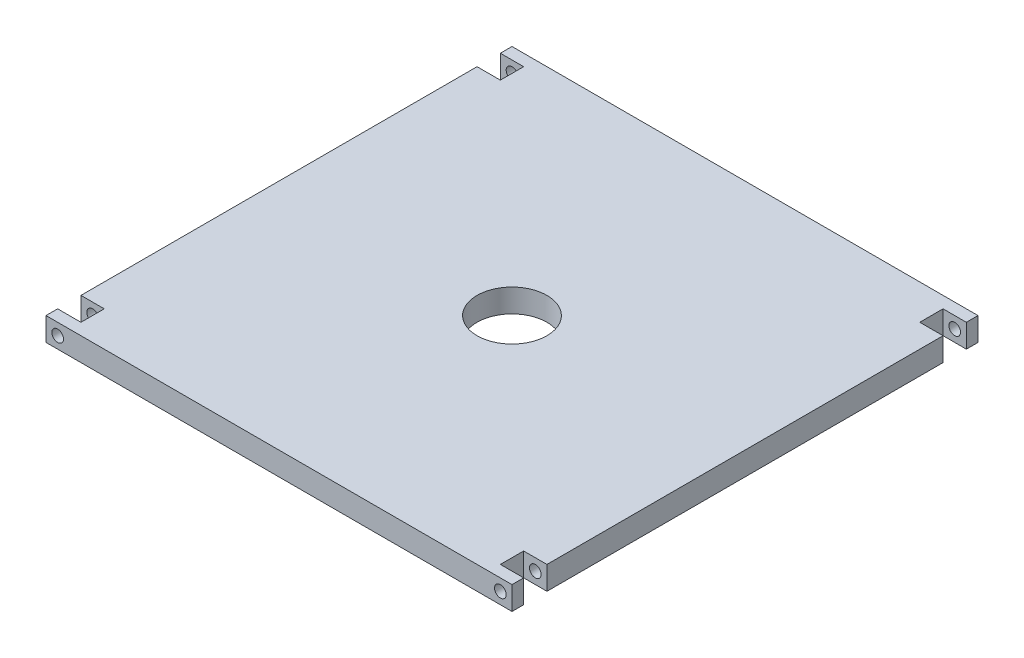
SolidWorks part; units mm, degrees
ref_plane "Plan de face" through (0, 0, 0) normal (0, 0, 1) x (1, 0, 0)
ref_plane "Plan de dessus" through (0, 0, 0) normal (0, 1, 0) x (1, 0, 0)
ref_plane "Plan de droite" through (0, 0, 0) normal (1, 0, 0) x (0, 0, -1)
sketch "Esquisse1" plane through (0, 0, 0) normal (0, 1, 0) x (1, 0, 0)
  line L0 (-100, 95) -> (-90, 95)
  line L1 (100, 100) -> (-100, 100)
  line L2 (100, 100) -> (100, 95)
  line L3 (100, -100) -> (15, -100)
  line L4 (-100, 100) -> (-100, 95)
  line L5 (100, 100) -> (-100, -100) construction
  line L6 (100, -100) -> (-100, 100) construction
  line L7 (-90, 95) -> (-90, 85)
  line L8 (-90, 85) -> (-100, 85)
  line L9 (-100, 85) -> (-100, -85)
  line L10 (46.6264, 0) -> (-32.5251, 0) construction
  line L11 (-90, -95) -> (-90, -85)
  line L12 (-100, -95) -> (-90, -95)
  line L13 (-90, -85) -> (-100, -85)
  line L14 (0, 41.9741) -> (0, -29.1916) construction
  line L15 (100, -95) -> (90, -95)
  line L16 (90, -95) -> (90, -85)
  line L17 (90, -85) -> (100, -85)
  line L18 (90, 95) -> (90, 85)
  line L19 (100, 95) -> (90, 95)
  line L20 (90, 85) -> (100, 85)
  line L21 (-100, -95) -> (-100, -100)
  line L22 (100, -95) -> (100, -100)
  line L23 (100, 85) -> (100, -85)
  line L24 (0, 0) -> (0, -148.2919) construction
  line L25 (-15, -100) -> (-100, -100)
  line L26 (15, -100) -> (-15, -100)
  circle A0 centre (0, 0) radius 15
  point P0 (0, 0)
  point P6 (-100, 95)
  point P29 (0, -100)
  dimension "D6" = 30
  dimension "D1" = 200
  dimension "D2" = 200
  dimension "D3" = 5
  dimension "D4" = 10
  dimension "D5" = 10
extrude "BASE" add sketch "Esquisse1" along normal blind 10
sketch "Esquisse2" plane through (0, 0, 100) normal (0, 0, 1) x (1, 0, 0)
  line L0 (0, 18.3939) -> (0, -9.401) construction
  line L1 (-100, 5) -> (100, 5) construction
  line L2 (-100, 10) -> (-100, 0) construction
  line L3 (100, 10) -> (100, 0) construction
  circle A0 centre (-95, 5) radius 2.5
  circle A1 centre (95, 5) radius 2.5
  dimension "D2" = 5
  dimension "D1" = 5
extrude "Enlèv. mat.-Extru.1" cut sketch "Esquisse2" against normal through all
